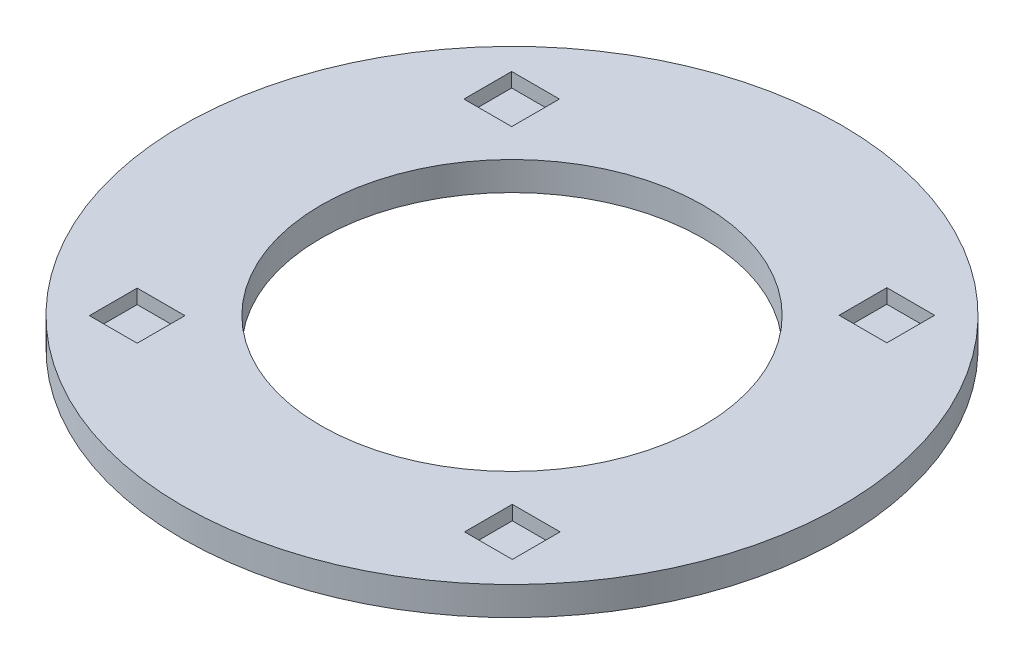
SolidWorks part; units mm, degrees
ref_plane "Front Plane" through (0, 0, 0) normal (0, 0, 1) x (1, 0, 0)
ref_plane "Top Plane" through (0, 0, 0) normal (0, 1, 0) x (1, 0, 0)
ref_plane "Right Plane" through (0, 0, 0) normal (1, 0, 0) x (0, 0, -1)
sketch "Sketch1" plane through (0, 0, 0) normal (0, 1, 0) x (1, 0, 0)
  circle A0 centre (0, 0) radius 34.5
  dimension "D1" = 69
extrude "Boss-Extrude1" add sketch "Sketch1" along normal blind 3
sketch "Sketch2" plane through (0, 3, 0) normal (0, 1, 0) x (1, 0, 0)
  line L0 (0, 0) -> (34.5, 0) construction
  line L1 (0, 0) -> (0, 34.5) construction
  line L2 (0, 0) -> (-34.5, 0) construction
  line L3 (0, 0) -> (0, -34.5) construction
  line L5 (-26.093, -3.0565) -> (-26.093, 3.1435)
  line L6 (-19.893, 3.1435) -> (-26.093, 3.1435)
  line L7 (-19.893, -3.0565) -> (-19.893, 3.1435)
  line L8 (-19.893, -3.0565) -> (-26.093, -3.0565)
  line L9 (-3.6156, 19.4138) -> (3.835, 19.4138)
  line L10 (-3.6156, 19.4138) -> (-3.6156, 26.8644)
  line L11 (-3.6156, 26.8644) -> (3.835, 26.8644)
  line L12 (3.835, 19.4138) -> (3.835, 26.8644)
  line L13 (-3.6156, 19.4138) -> (3.835, 26.8644) construction
  line L14 (-3.6156, 26.8644) -> (3.835, 19.4138) construction
  line L15 (3.2026, -26.1592) -> (-2.9974, -26.1592)
  line L16 (-2.9974, -19.9592) -> (-2.9974, -26.1592)
  line L17 (3.2026, -19.9592) -> (-2.9974, -19.9592)
  line L18 (3.2026, -19.9592) -> (3.2026, -26.1592)
  line L19 (26.3053, 3.1364) -> (26.3053, -3.0636)
  line L20 (20.1053, -3.0636) -> (26.3053, -3.0636)
  line L21 (20.1053, 3.1364) -> (20.1053, -3.0636)
  line L22 (20.1053, 3.1364) -> (26.3053, 3.1364)
  circle A0 centre (0, 0) radius 34.5 construction
  point P6 (0.1038, 23.1056)
  point P12 (0.1038, 23.1056)
sketch "Sketch3" plane through (0, 3, 0) normal (0, 1, 0) x (1, 0, 0)
  line L0 (16.1556, -7.0538) -> (16.1556, 6.8462)
  line L1 (7.0538, 30.0556) -> (-6.8462, 30.0556)
  line L2 (7.0538, 30.0556) -> (7.0538, 16.1556)
  line L3 (7.0538, 16.1556) -> (-6.8462, 16.1556)
  line L4 (-6.8462, 30.0556) -> (-6.8462, 16.1556)
  line L5 (7.0538, 30.0556) -> (-6.8462, 16.1556) construction
  line L6 (7.0538, 16.1556) -> (-6.8462, 30.0556) construction
  line L7 (30.0556, -7.0538) -> (16.1556, -7.0538)
  line L8 (30.0556, -7.0538) -> (30.0556, 6.8462)
  line L9 (30.0556, 6.8462) -> (16.1556, 6.8462)
  line L10 (-7.0538, -16.1556) -> (6.8462, -16.1556)
  line L11 (-7.0538, -30.0556) -> (-7.0538, -16.1556)
  line L12 (-7.0538, -30.0556) -> (6.8462, -30.0556)
  line L13 (6.8462, -30.0556) -> (6.8462, -16.1556)
  line L14 (-16.1556, 7.0538) -> (-16.1556, -6.8462)
  line L15 (-30.0556, 7.0538) -> (-16.1556, 7.0538)
  line L16 (-30.0556, 7.0538) -> (-30.0556, -6.8462)
  line L17 (-30.0556, -6.8462) -> (-16.1556, -6.8462)
  point P0 (0.1038, 23.1056)
  dimension "D1" = 13.9
  dimension "D2" = 13.9
  dimension "D3" = 4
sketch "Sketch4" plane through (0, 3, 0) normal (0, 1, 0) x (1, 0, 0)
  circle A0 centre (0, 0) radius 20
  dimension "D1" = 40
extrude "Cut-Extrude2" cut sketch "Sketch4" against normal through all
sketch "Sketch5" plane through (0, 3, 0) normal (0, 1, 0) x (1, 0, 0)
  line L0 (-23.1056, 7.0538) -> (-23.1056, 25.6199) construction
  line L1 (-16.1556, 7.0538) -> (-30.0556, 7.0538) construction
  line L2 (0.1038, 23.1056) -> (-25.6199, 23.1056) construction
  line L3 (0, 0) -> (-24.416, 24.3743) construction
  line L4 (22.1032, 17.1367) -> (22.1032, 22.1367)
  line L5 (-17.1367, 22.1032) -> (-22.1367, 22.1032)
  line L6 (-17.1367, 22.1032) -> (-17.1367, 17.1032)
  line L7 (-17.1367, 17.1032) -> (-22.1367, 17.1032)
  line L8 (-22.1367, 22.1032) -> (-22.1367, 17.1032)
  line L9 (-17.1367, 22.1032) -> (-22.1367, 17.1032) construction
  line L10 (-17.1367, 17.1032) -> (-22.1367, 22.1032) construction
  line L11 (17.1032, 17.1367) -> (17.1032, 22.1367)
  line L12 (22.1032, 17.1367) -> (17.1032, 17.1367)
  line L13 (22.1032, 22.1367) -> (17.1032, 22.1367)
  line L14 (17.1367, -22.1032) -> (22.1367, -22.1032)
  line L15 (17.1367, -17.1032) -> (22.1367, -17.1032)
  line L16 (17.1367, -22.1032) -> (17.1367, -17.1032)
  line L17 (22.1367, -22.1032) -> (22.1367, -17.1032)
  line L18 (-22.1032, -17.1367) -> (-22.1032, -22.1367)
  line L19 (-17.1032, -17.1367) -> (-17.1032, -22.1367)
  line L20 (-22.1032, -17.1367) -> (-17.1032, -17.1367)
  line L21 (-22.1032, -22.1367) -> (-17.1032, -22.1367)
  circle A0 centre (0, 0) radius 34.5 construction
  point P12 (-19.6367, 19.6032)
  dimension "D1" = 5
  dimension "D2" = 5
  dimension "D3" = 4
extrude "Cut-Extrude3" cut sketch "Sketch5" against normal blind 1.5
